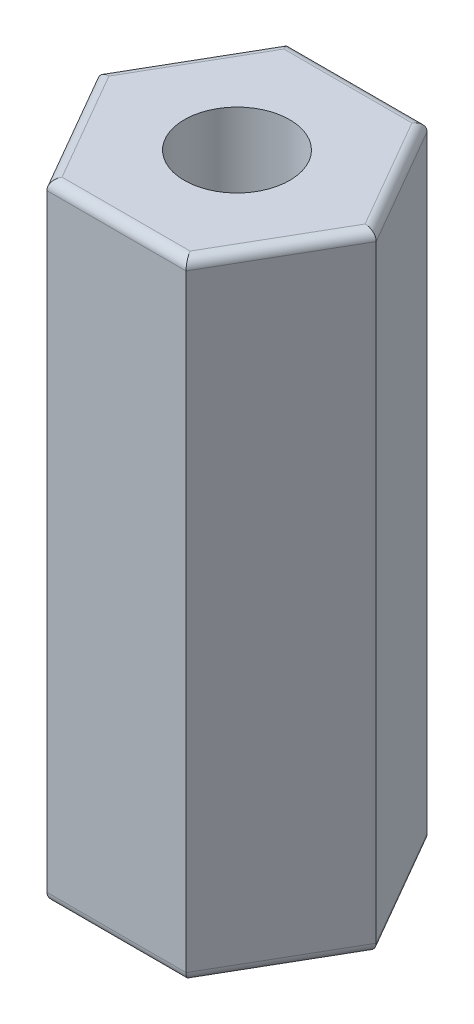
SolidWorks part; units mm, degrees
material "201.0-T43 Molde de fundição com isolamento (SS)"
ref_plane "Plano frontal" through (0, 0, 0) normal (0, 0, 1) x (1, 0, 0)
ref_plane "Plano superior" through (0, 0, 0) normal (0, 1, 0) x (1, 0, 0)
ref_plane "Plano direito" through (0, 0, 0) normal (1, 0, 0) x (0, 0, -1)
sketch "Esboço1" plane through (0, 0, 0) normal (0, 1, 0) x (1, 0, 0)
  line L1 (2.8868, 0) -> (1.4434, 2.5)
  line L2 (1.4434, 2.5) -> (-1.4434, 2.5)
  line L3 (-1.4434, 2.5) -> (-2.8868, 0)
  line L4 (-2.8868, 0) -> (-1.4434, -2.5)
  line L5 (-1.4434, -2.5) -> (1.4434, -2.5)
  line L6 (1.4434, -2.5) -> (2.8868, 0)
  circle A0 centre (0, 0) radius 2.5 construction
  dimension "D1" = 5
extrude "Ressalto-extrusão1" add sketch "Esboço1" along normal blind 13
fillet "Filete1" radius 0.2 12 edges at (0, 13, -2.5) (-2.1651, 13, -1.25) (-2.1651, 13, 1.25) (0, 13, 2.5) (2.1651, 13, 1.25) (2.1651, 13, -1.25) (0, 0, 2.5) (-2.1651, 0, 1.25) (-2.1651, 0, -1.25) (0, 0, -2.5) (2.1651, 0, -1.25) (2.1651, 0, 1.25)
sketch "Esboço2" plane through (0, 0, 0) normal (0, -1, 0) x (1, 0, 0)
  circle A0 centre (0, 0) radius 1.0922
  dimension "D1" = 2.1844
sketch "Esboço3" plane through (0, 13, 0) normal (0, 1, 0) x (1, 0, 0)
  circle A0 centre (0, 0) radius 1.0922
extrude "Corte-extrusão1" cut sketch "Esboço3" against normal blind 5
extrude "Corte-extrusão2" cut sketch "Esboço2" against normal blind 5 contours A0
